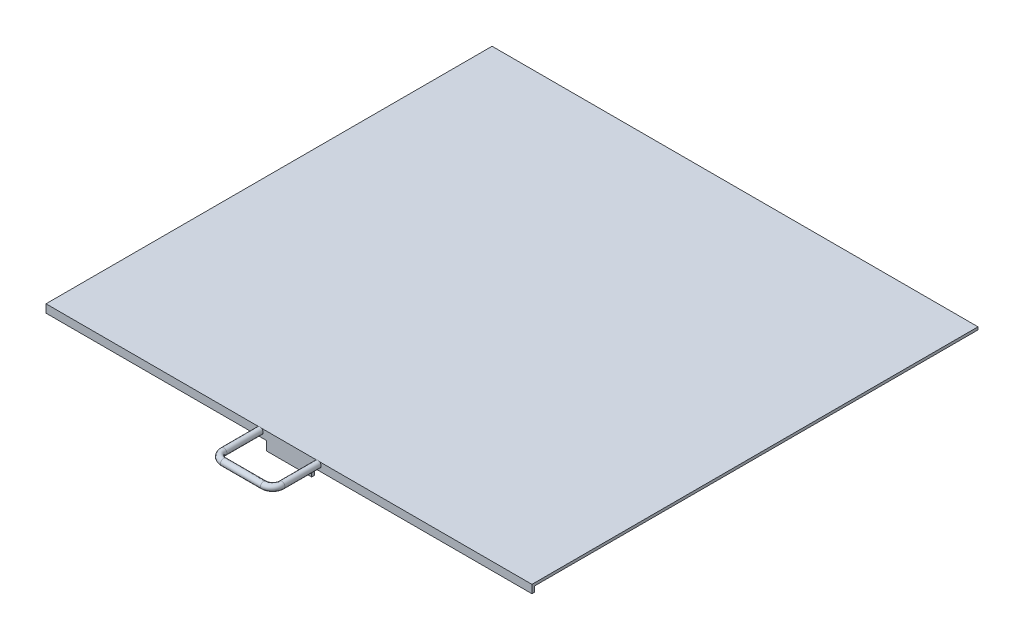
SolidWorks part; units mm, degrees
ref_plane "Front Plane" through (0, 0, 0) normal (0, 0, 1) x (1, 0, 0)
ref_plane "Top Plane" through (0, 0, 0) normal (0, 1, 0) x (1, 0, 0)
ref_plane "Right Plane" through (0, 0, 0) normal (1, 0, 0) x (0, 0, -1)
sketch "Sketch1" plane through (0, 0, 0) normal (0, 1, 0) x (1, 0, 0)
  line L1 (-134, -123) -> (134, -123)
  line L2 (-134, -123) -> (-134, 123)
  line L3 (-134, 123) -> (134, 123)
  line L4 (134, -123) -> (134, 123)
  line L5 (-134, -123) -> (134, 123) construction
  line L6 (-134, 123) -> (134, -123) construction
  point P0 (0, 0)
  dimension "D1" = 268
  dimension "D2" = 246
extrude "Boss-Extrude1" add sketch "Sketch1" along normal blind 1.5
sketch "Sketch2" plane through (0, 0, 123) normal (0, 0, 1) x (1, 0, 0)
  line L0 (0, 0) -> (0, -5.0268) construction
  line L1 (-134, 0) -> (134, 0)
  line L2 (-134, 0) -> (-134, -3)
  line L3 (-134, -3) -> (-12.5, -3)
  line L4 (134, 0) -> (134, -3)
  line L5 (12.5, -3) -> (134, -3)
  line L6 (-12.5, -8) -> (12.5, -8)
  line L7 (-12.5, -8) -> (-12.5, -3)
  line L9 (12.5, -8) -> (12.5, -3)
  line L10 (-12.5, -8) -> (12.5, -3) construction
  line L11 (-12.5, -3) -> (12.5, -8) construction
  point P5 (0, -5.5)
  dimension "D1" = 3
  dimension "D2" = 25
  dimension "D3" = 5
extrude "Boss-Extrude2" add sketch "Sketch2" against normal blind 1.5
sketch "Sketch3" plane through (0, 0, 0) normal (0, 1, 0) x (1, 0, 0)
  line L0 (0, 0) -> (0, -184.254) construction
  line L1 (-16, -123) -> (-16, -143)
  line L2 (-134, -123) -> (134, -123) construction
  line L3 (-11, -148) -> (11, -148)
  line L4 (16, -143) -> (16, -123)
  arc A0 (-16, -143) -> (-11, -148) centre (-11, -143) ccw
  arc A1 (11, -148) -> (16, -143) centre (11, -143) ccw
  point P12 (0, 0)
  dimension "D1" = 5
  dimension "D2" = 22
  dimension "D3" = 20
sweep "Sweep1" add path "Sketch3" circular profile diameter 3.5 parameters "D3"=3.5
